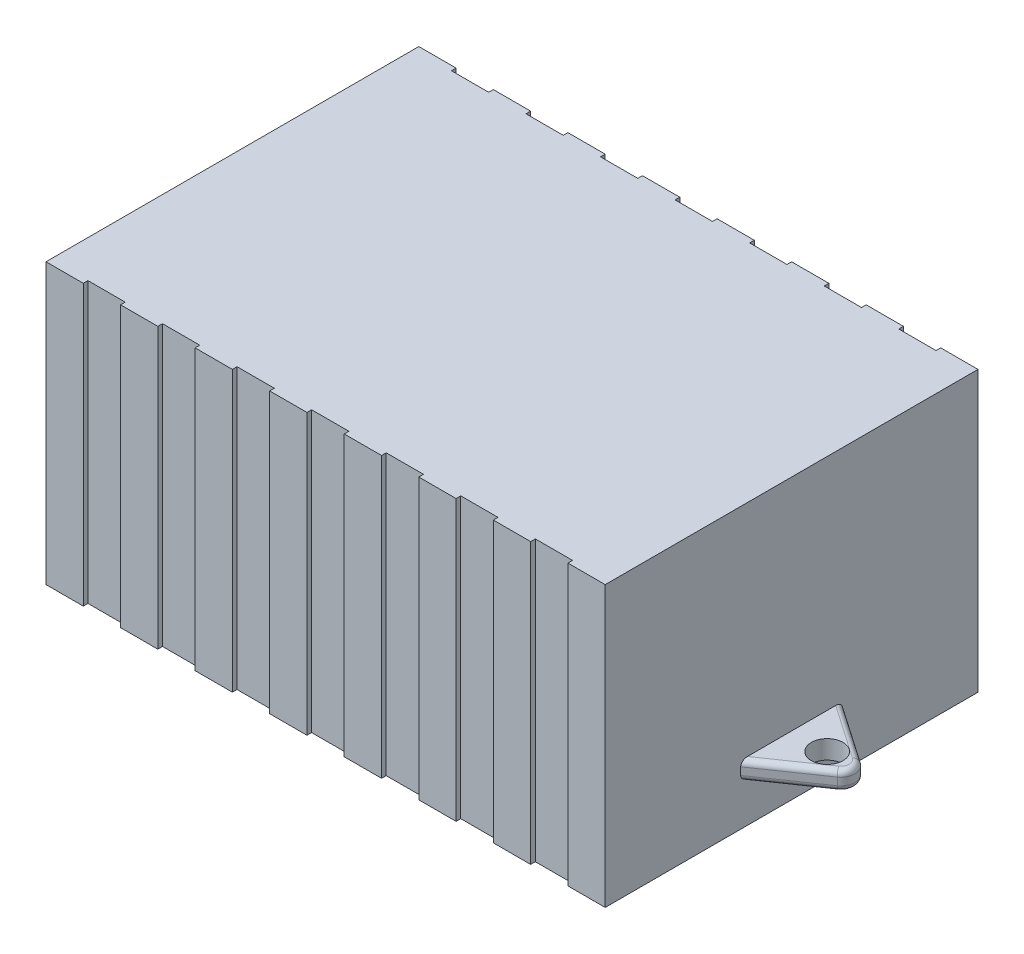
SolidWorks part; units mm, degrees
ref_plane "Front Plane" through (0, 0, 0) normal (0, 0, 1) x (1, 0, 0)
ref_plane "Top Plane" through (0, 0, 0) normal (0, 1, 0) x (1, 0, 0)
ref_plane "Right Plane" through (0, 0, 0) normal (1, 0, 0) x (0, 0, -1)
sketch "Sketch2" plane through (0, 0, 0) normal (0, 1, 0) x (1, 0, 0)
  line L0 (0, 0) -> (381, 0) construction
  line L1 (-381, 254) -> (-330.2, 254)
  line L2 (-381, 254) -> (-381, -254)
  line L4 (381, 254) -> (381, -254)
  line L5 (330.2, -254) -> (381, -254)
  line L6 (228.6, -254) -> (279.4, -254)
  line L7 (-330.2, 247.65) -> (-330.2, 254)
  line L8 (-330.2, 247.65) -> (-279.4, 247.65)
  line L9 (-279.4, 247.65) -> (-279.4, 254)
  line L10 (127, -254) -> (177.8, -254)
  line L11 (-228.6, 247.65) -> (-228.6, 254)
  line L12 (-228.6, 247.65) -> (-177.8, 247.65)
  line L13 (-177.8, 247.65) -> (-177.8, 254)
  line L14 (25.4, -254) -> (76.2, -254)
  line L15 (-127, 247.65) -> (-127, 254)
  line L16 (-127, 247.65) -> (-76.2, 247.65)
  line L17 (-76.2, 247.65) -> (-76.2, 254)
  line L18 (-76.2, -254) -> (-25.4, -254)
  line L19 (-25.4, 247.65) -> (-25.4, 254)
  line L20 (-25.4, 247.65) -> (25.4, 247.65)
  line L21 (25.4, 247.65) -> (25.4, 254)
  line L22 (-177.8, -254) -> (-127, -254)
  line L23 (76.2, 247.65) -> (76.2, 254)
  line L24 (76.2, 247.65) -> (127, 247.65)
  line L25 (127, 247.65) -> (127, 254)
  line L26 (-279.4, -254) -> (-228.6, -254)
  line L27 (177.8, 247.65) -> (177.8, 254)
  line L28 (177.8, 247.65) -> (228.6, 247.65)
  line L29 (228.6, 247.65) -> (228.6, 254)
  line L30 (381, -247.65) -> (381, -254)
  line L31 (279.4, 247.65) -> (279.4, 254)
  line L32 (279.4, 247.65) -> (330.2, 247.65)
  line L33 (330.2, 247.65) -> (330.2, 254)
  line L34 (330.2, -247.65) -> (330.2, -254)
  line L35 (381, 247.65) -> (381, 254)
  line L36 (-279.4, 254) -> (-228.6, 254)
  line L37 (-177.8, 254) -> (-127, 254)
  line L38 (-76.2, 254) -> (-25.4, 254)
  line L39 (25.4, 254) -> (76.2, 254)
  line L40 (127, 254) -> (177.8, 254)
  line L41 (228.6, 254) -> (279.4, 254)
  line L42 (330.2, 254) -> (381, 254)
  line L49 (279.4, -247.65) -> (330.2, -247.65)
  line L50 (279.4, -247.65) -> (279.4, -254)
  line L51 (228.6, -247.65) -> (228.6, -254)
  line L52 (177.8, -247.65) -> (228.6, -247.65)
  line L53 (177.8, -247.65) -> (177.8, -254)
  line L54 (127, -247.65) -> (127, -254)
  line L55 (76.2, -247.65) -> (127, -247.65)
  line L56 (76.2, -247.65) -> (76.2, -254)
  line L57 (25.4, -247.65) -> (25.4, -254)
  line L58 (-25.4, -247.65) -> (25.4, -247.65)
  line L59 (-25.4, -247.65) -> (-25.4, -254)
  line L60 (-76.2, -247.65) -> (-76.2, -254)
  line L61 (-127, -247.65) -> (-76.2, -247.65)
  line L62 (-127, -247.65) -> (-127, -254)
  line L63 (-177.8, -247.65) -> (-177.8, -254)
  line L64 (-228.6, -247.65) -> (-177.8, -247.65)
  line L65 (-228.6, -247.65) -> (-228.6, -254)
  line L66 (-279.4, -247.65) -> (-279.4, -254)
  line L67 (-330.2, -247.65) -> (-279.4, -247.65)
  line L68 (-330.2, -247.65) -> (-330.2, -254)
  line L69 (-381, -254) -> (-330.2, -254)
  point P0 (0, 0)
  point P80 (381, 0)
  point P81 (-381, 0)
  dimension "D1" = 762
  dimension "D3" = 6.35
  dimension "D5" = 15
extrude "Boss-Extrude1" add sketch "Sketch2" along normal blind 381 contours L0 L2 L69 L68 L67 L66 L26 L65 L64 L63 L22 L62 L61 L60 L18 L59 L58 L57 L14 L56 L55 L54 L10 L53 L52 L51 L6 L50 L49 L34 L5 L4 | L2 L0 L4 L42 L33 L32 L31 L41 L29 L28 L27 L40 L25 L24 L23 L39 L21 L20 L19 L38 L17 L16 L15 L37 L13 L12 L11 L36 L9 L8 L7 L1
ref_plane "Plane1" through (0, 68.58, 0) normal (0, -1, 0) x (-1, 0, 0)
sketch "Sketch3" plane through (0, 68.58, 0) normal (0, -1, 0) x (-1, 0, 0)
  line L0 (-381, 0) -> (-448.339, 0) construction
  line L2 (-458.8924, -15.6841) -> (-381, -69.3828)
  line L3 (-381, 254) -> (-381, -254) construction
  line L4 (-458.8924, 15.6841) -> (-381, 69.3828)
  line L5 (-381, 69.3828) -> (-381, -69.3828)
  arc A0 (-458.8924, 15.6841) -> (-458.8924, -15.6841) centre (-448.0799, 0) ccw
  point P10 (-481.6429, 0)
  dimension "D1" = 19.05
extrude "Boss-Extrude2" add sketch "Sketch3" along normal mid plane 25.4
sketch "Sketch4" plane through (0, 81.28, 0) normal (0, 1, 0) x (1, 0, 0)
  circle A0 centre (429.4966, 0) radius 21.5923
  point P2 (0, 0)
  point P3 (0, 0)
  point P4 (0, 0)
  point P5 (429.4966, 0)
  dimension "D1" = 43.1846
extrude "Cut-Extrude1" cut sketch "Sketch4" against normal blind 25.4
fillet "Fillet1" radius 7.62 6 edges at (419.9462, 55.88, -42.5335) (467.1299, 55.88, 0) (419.9462, 81.28, -42.5335) (467.1299, 81.28, 0) (419.9462, 55.88, 42.5335) (419.9462, 81.28, 42.5335)
sketch "Sketch5" plane through (0, 0, 0) normal (0, -1, 0) x (1, 0, 0)
  line L0 (-381, 0) -> (381, 0) construction
  circle A1 centre (-314.062, -177.8) radius 25.4
  circle A2 centre (244.738, -177.8) radius 25.4
  circle A3 centre (244.738, 177.8) radius 25.4
  circle A4 centre (-314.062, 177.8) radius 25.4
  dimension "D1" = 558.8
  dimension "D2" = 50.8
  dimension "D3" = 50.8
  dimension "D4" = 177.8
extrude "Cut-Extrude2" cut sketch "Sketch5" against normal blind 127
